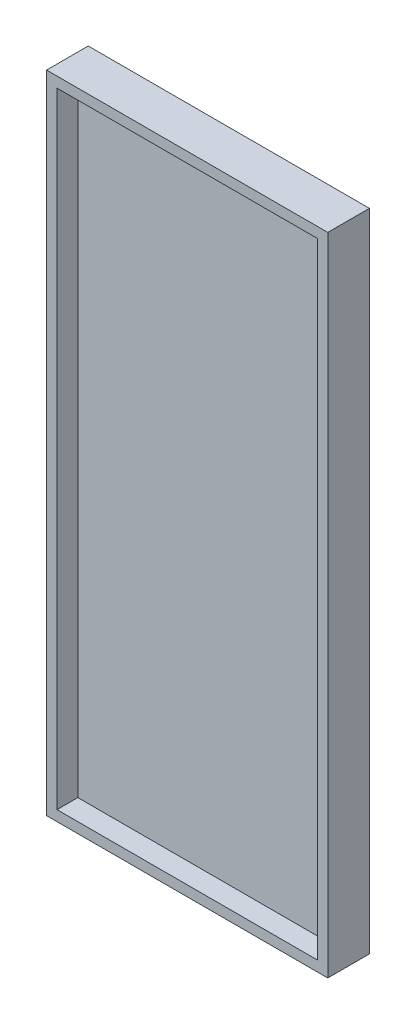
SolidWorks part; units mm, degrees
ref_plane "Front Plane" through (0, 0, 0) normal (0, 0, 1) x (1, 0, 0)
ref_plane "Top Plane" through (0, 0, 0) normal (0, 1, 0) x (1, 0, 0)
ref_plane "Right Plane" through (0, 0, 0) normal (1, 0, 0) x (0, 0, -1)
sketch "Sketch1" plane through (0, 0, 0) normal (0, 0, 1) x (1, 0, 0)
  line L1 (-13.5, 31) -> (13.5, 31)
  line L2 (-13.5, 31) -> (-13.5, -31)
  line L3 (-13.5, -31) -> (13.5, -31)
  line L4 (13.5, 31) -> (13.5, -31)
  line L5 (-13.5, 31) -> (13.5, -31) construction
  line L6 (-13.5, -31) -> (13.5, 31) construction
  point P0 (0, 0)
  dimension "D1" = 62
  dimension "D2" = 27
extrude "Boss-Extrude1" add sketch "Sketch1" along normal blind 2
sketch "Sketch6" plane through (0, 0, 2) normal (0, 0, 1) x (1, 0, 0)
  line L0 (-13.5, -31) -> (13.5, -31) construction
  line L1 (-13.5, 31) -> (13.5, 31)
  line L2 (-13.5, 31) -> (-13.5, -31)
  line L3 (-13.5, -31) -> (13.5, -31)
  line L4 (13.5, 31) -> (13.5, -31)
  line L5 (-13.5, 31) -> (13.5, -31) construction
  line L6 (-13.5, -31) -> (13.5, 31) construction
  line L8 (-12.5, 30) -> (12.5, 30)
  line L9 (-12.5, 30) -> (-12.5, -30)
  line L10 (-12.5, -30) -> (12.5, -30)
  line L11 (12.5, 30) -> (12.5, -30)
  line L12 (-12.5, 30) -> (12.5, -30) construction
  line L13 (-12.5, -30) -> (12.5, 30) construction
  point P0 (0, 0)
  point P8 (0, 0)
  dimension "D1" = 27
  dimension "D2" = 1
  dimension "D3" = 1
extrude "Boss-Extrude2" add sketch "Sketch6" along normal blind 2 contours L2 L1 L4 L3 | L9 L8 L11 L10
